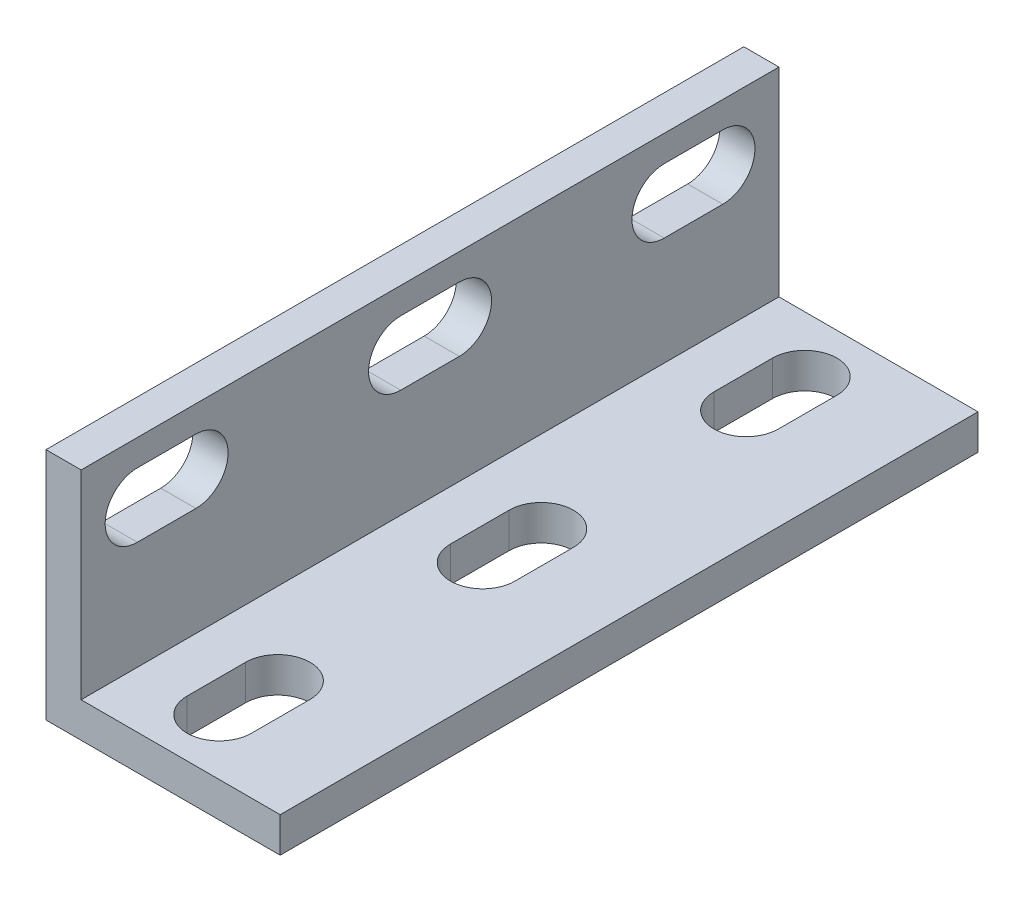
SolidWorks part; units mm, degrees
material "6061 Alloy"
ref_plane "Front Plane" through (0, 0, 0) normal (0, 0, 1) x (1, 0, 0)
ref_plane "Top Plane" through (0, 0, 0) normal (0, 1, 0) x (1, 0, 0)
ref_plane "Right Plane" through (0, 0, 0) normal (1, 0, 0) x (0, 0, -1)
sketch "Sketch1" plane through (0, 0, 0) normal (0, 0, 1) x (1, 0, 0)
  line L0 (0, 20) -> (0, 0)
  line L1 (0, 0) -> (20, 0)
  dimension "D1" = 20
  dimension "D2" = 20
extrude "Extrude-Thin1" add sketch "Sketch1" along normal blind 59.6 thin thin type one direction reverse wall 3
sketch "Sketch2" plane through (0, 3, 0) normal (0, 1, 0) x (1, 0, 0)
  line L0 (10, -54.8) -> (10, -49.8) construction
  line L1 (7.25, -54.8) -> (7.25, -49.8)
  line L2 (12.75, -54.8) -> (12.75, -49.8)
  line L3 (20, -59.6) -> (20, 0) construction
  line L4 (3, -59.6) -> (3, 0) construction
  line L5 (3, -59.6) -> (20, -59.6) construction
  line L6 (10, -27.3) -> (10, -32.3) construction
  line L7 (12.75, -27.3) -> (12.75, -32.3)
  line L8 (7.25, -27.3) -> (7.25, -32.3)
  line L9 (10, -9.8) -> (10, -4.8) construction
  line L10 (7.25, -9.8) -> (7.25, -4.8)
  line L11 (12.75, -9.8) -> (12.75, -4.8)
  arc A0 (7.25, -54.8) -> (12.75, -54.8) centre (10, -54.8) ccw
  arc A1 (12.75, -49.8) -> (7.25, -49.8) centre (10, -49.8) ccw
  arc A2 (12.75, -27.3) -> (7.25, -27.3) centre (10, -27.3) ccw
  arc A3 (7.25, -32.3) -> (12.75, -32.3) centre (10, -32.3) ccw
  arc A4 (7.25, -9.8) -> (12.75, -9.8) centre (10, -9.8) ccw
  arc A5 (12.75, -4.8) -> (7.25, -4.8) centre (10, -4.8) ccw
  point P2 (10, -52.3)
  point P15 (10, -29.8)
  point P20 (10, -7.3)
  point P29 (10, -35.05)
  point P30 (10, -12.55)
  dimension "D1" = 7.25
  dimension "D2" = 4.25
  dimension "D3" = 4.8
  dimension "D4" = 9.8
  dimension "D5" = 24.55
  dimension "D6" = 47.05
extrude "Cut-Extrude1" cut sketch "Sketch2" against normal blind 3
sketch "Sketch3" plane through (3, 0, 0) normal (1, 0, 0) x (0, 0, -1)
  line L0 (-54.8, 15) -> (-49.8, 15) construction
  line L1 (-54.8, 17.75) -> (-49.8, 17.75)
  line L2 (-54.8, 12.25) -> (-49.8, 12.25)
  line L3 (-32.3, 15) -> (-27.3, 15) construction
  line L4 (-32.3, 17.75) -> (-27.3, 17.75)
  line L5 (-32.3, 12.25) -> (-27.3, 12.25)
  line L6 (-9.8, 15) -> (-4.8, 15) construction
  line L7 (-9.8, 17.75) -> (-4.8, 17.75)
  line L8 (-9.8, 12.25) -> (-4.8, 12.25)
  line L9 (-4.8, 3) -> (-9.8, 3) construction
  line L10 (-59.6, 20) -> (0, 20) construction
  arc A0 (-54.8, 17.75) -> (-54.8, 12.25) centre (-54.8, 15) ccw
  arc A1 (-49.8, 12.25) -> (-49.8, 17.75) centre (-49.8, 15) ccw
  arc A2 (-32.3, 17.75) -> (-32.3, 12.25) centre (-32.3, 15) ccw
  arc A3 (-27.3, 12.25) -> (-27.3, 17.75) centre (-27.3, 15) ccw
  arc A4 (-9.8, 17.75) -> (-9.8, 12.25) centre (-9.8, 15) ccw
  arc A5 (-4.8, 12.25) -> (-4.8, 17.75) centre (-4.8, 15) ccw
  point P2 (-52.3, 15)
  point P7 (-29.8, 15)
  point P14 (-7.3, 15)
  dimension "D1" = 2.75
  dimension "D2" = 0
  dimension "D3" = 0
  dimension "D4" = 2.25
  dimension "D5" = 17.5
extrude "Cut-Extrude2" cut sketch "Sketch3" against normal blind 3
